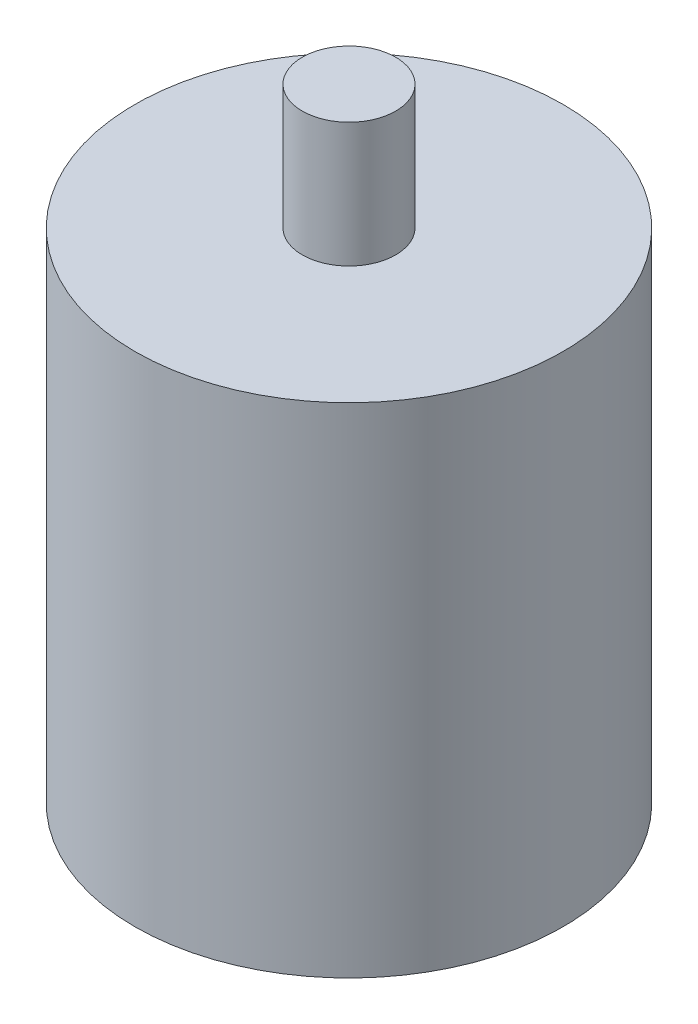
SolidWorks part; units mm, degrees
ref_plane "Front Plane" through (0, 0, 0) normal (0, 0, 1) x (1, 0, 0)
ref_plane "Top Plane" through (0, 0, 0) normal (0, 1, 0) x (1, 0, 0)
ref_plane "Right Plane" through (0, 0, 0) normal (1, 0, 0) x (0, 0, -1)
sketch "Sketch1" plane through (0, 0, 0) normal (0, 1, 0) x (1, 0, 0)
  circle A0 centre (0, 0) radius 13.75
  dimension "D1" = 27.5
extrude "Boss-Extrude1" add sketch "Sketch1" along normal blind 32
sketch "Sketch2" plane through (0, 32, 0) normal (0, 1, 0) x (1, 0, 0)
  circle A0 centre (0, 0) radius 3
  dimension "D1" = 6
extrude "Boss-Extrude2" add sketch "Sketch2" along normal blind 8
